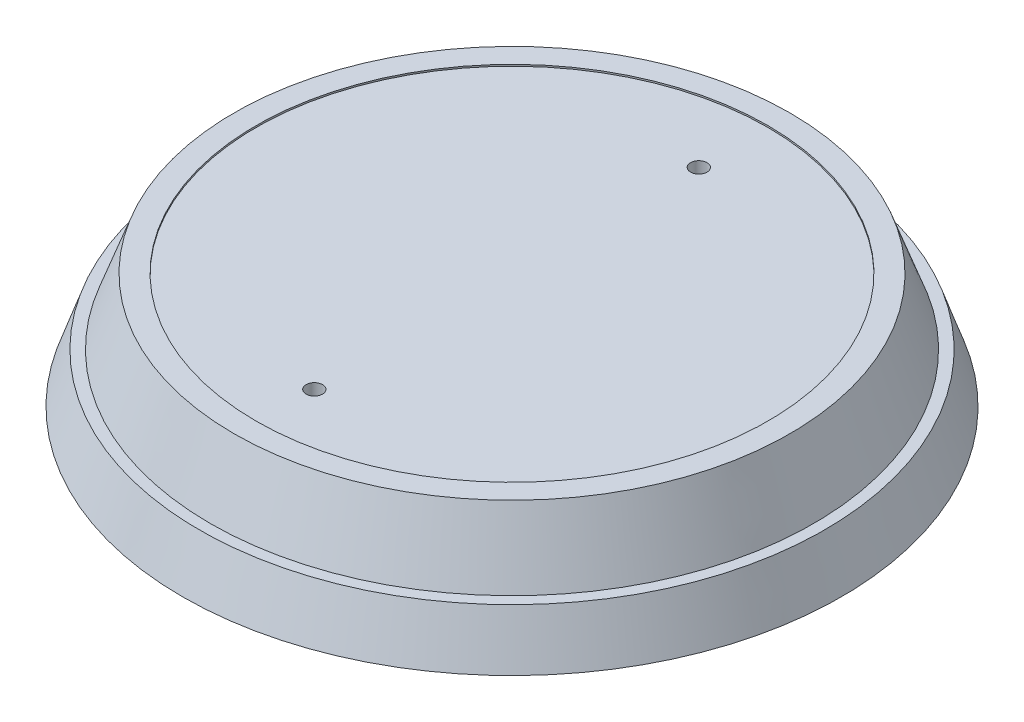
SolidWorks part; units mm, degrees
ref_plane "Front Plane" through (0, 0, 0) normal (0, 0, 1) x (1, 0, 0)
ref_plane "Top Plane" through (0, 0, 0) normal (0, 1, 0) x (1, 0, 0)
ref_plane "Right Plane" through (0, 0, 0) normal (1, 0, 0) x (0, 0, -1)
sketch "Sketch1" plane through (0, 0, 0) normal (0, 0, 1) x (1, 0, 0)
  line L0 (0, 0) -> (0, 4.8509)
  line L1 (0, 4.8509) -> (23.3, 4.8509)
  line L2 (23.3, 4.8509) -> (23.3, 5.5009)
  line L3 (23.3, 5.5009) -> (25.3, 5.5009)
  line L4 (25.3, 5.5009) -> (27.4586, -0.4991)
  line L5 (27.4586, -0.4991) -> (28.4586, -0.4991)
  line L6 (28.4586, -0.4991) -> (30, -5)
  line L7 (30, -5) -> (15, -5)
  line L8 (15, -5) -> (15, 0)
  line L9 (0, 0) -> (15, 0)
  point P3 (0, 0)
  point P12 (27.4586, -0.4991)
  dimension "D1" = 15
  dimension "D2" = 15
  dimension "D3" = 23.3
  dimension "D4" = 2
  dimension "D5" = 0.65
  dimension "D6" = 6
  dimension "D7" = 1
  dimension "D8" = 5
revolve "Revolve1" add sketch "Sketch1" angle 360 about L0
sketch "Sketch2" plane through (0, 4.8509, 0) normal (0, 1, 0) x (1, 0, 0)
  circle A0 centre (0, 0) radius 23.5
  dimension "D1" = 47
extrude "Boss-Extrude1" add sketch "Sketch2" along normal blind 0.5
sketch "Sketch3" plane through (0, 5.3509, 0) normal (0, 1, 0) x (1, 0, 0)
  circle A0 centre (0, 17.0047) radius 0.75
  circle A1 centre (0, -17.9953) radius 0.75
  dimension "D2" = 1.5
  dimension "D3" = 1.5
  dimension "D1" = 35
extrude "Cut-Extrude1" cut sketch "Sketch3" against normal blind 5
